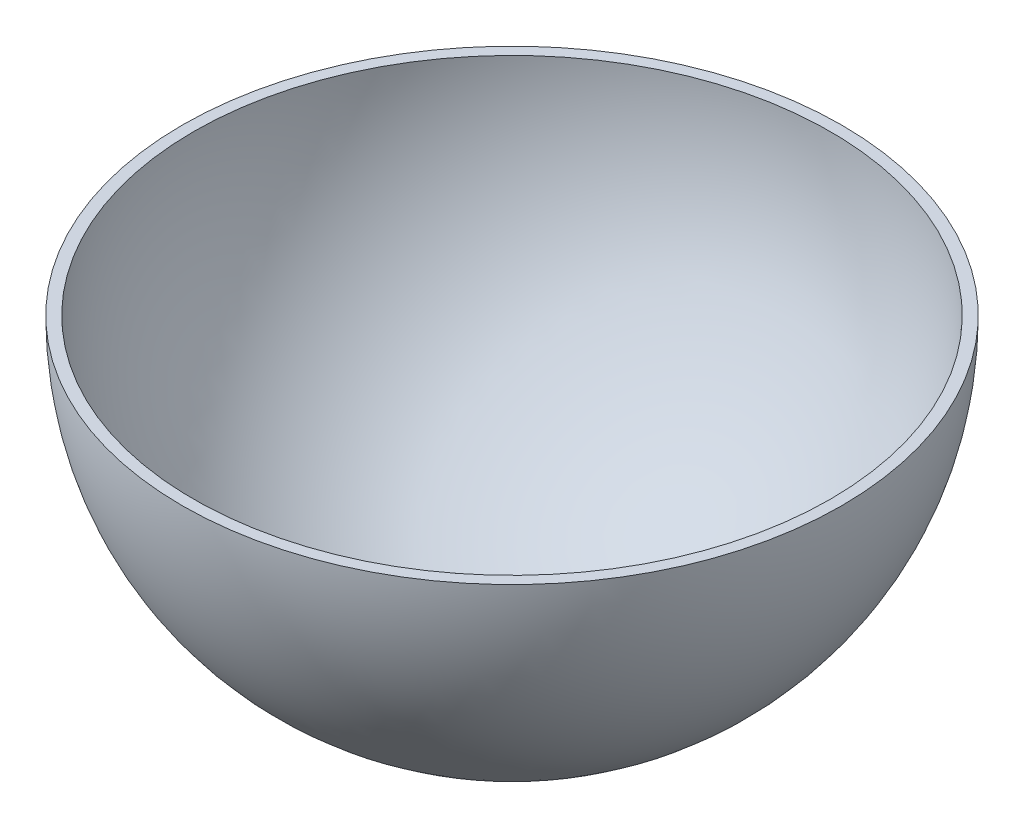
SolidWorks part; units mm, degrees
ref_plane "Front Plane" through (0, 0, 0) normal (0, 0, 1) x (1, 0, 0)
ref_plane "Top Plane" through (0, 0, 0) normal (0, 1, 0) x (1, 0, 0)
ref_plane "Right Plane" through (0, 0, 0) normal (1, 0, 0) x (0, 0, -1)
sketch "Sketch1" plane through (0, 0, 0) normal (0, 0, 1) x (1, 0, 0)
  line L0 (35, 0) -> (0, 0) construction
  line L1 (0, 0) -> (0, -35) construction
  line L2 (35, 0) -> (0, 0) construction
  line L3 (35, 0) -> (0, 0) construction
  line L4 (35, 0) -> (33.8, 0)
  line L6 (0, -35) -> (0, -33.8)
  arc A0 (35, 0) -> (0, -35) centre (0, 0) cw
  arc A1 (33.8, 0) -> (0, -33.8) centre (0, 0) cw
  arc A2 (35, 0) -> (34.9996, -0.1567) centre (0, 0) cw construction
  arc A3 (33.8, 0) -> (33.7997, -0.1514) centre (0, 0) cw construction
  point P9 (0, 35)
  point P10 (3.5041, -34.8114)
  point P11 (-11.3059, 31.853)
  point P12 (-30.2202, -17.6562)
  point P13 (-32.7627, 12.3129)
  point P14 (4.1145, -34.7397)
  point P15 (-23.4925, -25.9443)
  point P16 (33.4053, -5.1505)
  point P17 (0.4217, -33.7975)
  point P18 (34.9955, -0.5423)
  point P19 (34.9489, 1.8262)
  point P20 (33.7204, -2.4)
  point P21 (34.9688, 1.477)
  point P22 (33.7514, -1.877)
  point P23 (35.0888, 5.3991)
  point P24 (0, 0)
  point P26 (35, 0)
  dimension "D1" = 35
  dimension "D2" = 1.2
revolve "Revolve4" add sketch "Sketch1" angle 360 about L1
